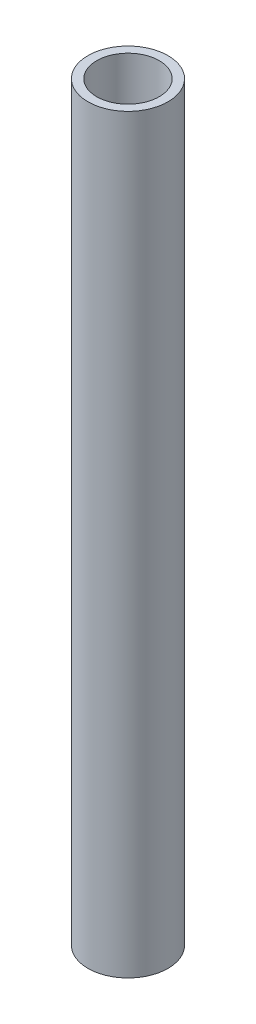
SolidWorks part; units mm, degrees
ref_plane "Спереди" through (0, 0, 0) normal (0, 0, 1) x (1, 0, 0)
ref_plane "Сверху" through (0, 0, 0) normal (0, 1, 0) x (1, 0, 0)
ref_plane "Справа" through (0, 0, 0) normal (1, 0, 0) x (0, 0, -1)
sketch "Эскиз1" plane through (0, 0, 0) normal (0, 1, 0) x (1, 0, 0)
  circle A0 centre (0, 0) radius 12.5
  circle A1 centre (0, 0) radius 16
extrude "Вытянуть1" add sketch "Эскиз1" along normal blind 300
